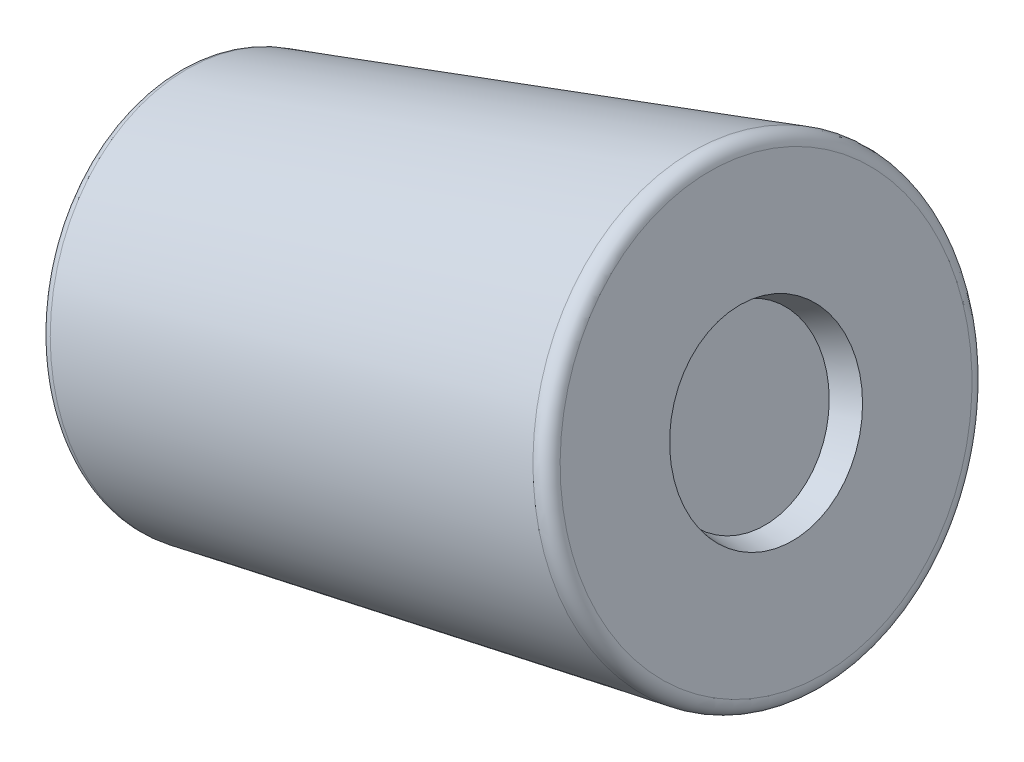
SolidWorks part; units mm, degrees
ref_plane "Plan1" through (0, 0, 0) normal (0, 0, 1) x (1, 0, 0)
ref_plane "Plan2" through (0, 0, 0) normal (0, 1, 0) x (1, 0, 0)
ref_plane "Plan3" through (0, 0, 0) normal (1, 0, 0) x (0, 0, -1)
sketch "Esquisse1" plane through (0, 0, 0) normal (0, 0, 1) x (1, 0, 0)
  line L0 (8.3922, 23.5728) -> (-71.107, 0) construction
  line L1 (-3.9021, 19.9274) -> (-13.911, 16.9596)
  line L2 (0, 0) -> (-86.5472, 0) construction
  line L3 (-14, 15.1559) -> (-15, 14.8879) construction
  line L4 (-13.5693, 13.5483) -> (-14, 15.1559) construction
  line L7 (-2.765, 16.0924) -> (-13.132, 13.6513)
  line L8 (-2.765, 16.0924) -> (-3.9021, 19.9274)
  line L9 (-13.911, 16.9596) -> (-13.132, 13.6513)
  line L11 (-71.107, 0) -> (5.4225, 18.0203) construction
  line L12 (-2.868, 16.0681) -> (-13.5693, 13.5483) construction
  line L13 (-2.868, 16.0681) -> (-3.3856, 18) construction
  point P6 (-14, 15.1559)
  dimension "D2" = 0.5
  dimension "D3" = 4
revolve "Base-Révolution" add sketch "Esquisse1" angle 360 about L0
sketch "Esquisse3" plane through (1.8473, 0.5375, 0) normal (0.9587, 0.2843, 0) x (0, 0, -1)
  circle A0 centre (0, 20.2243) radius 1.75
  circle A2 centre (0, 20.2243) radius 4 construction
  dimension "D1" = 3.5
extrude "Enlèv. mat.-Extru.1" cut sketch "Esquisse3" against normal blind 0.5 draft 16
fillet "Congé1" radius 0.25
